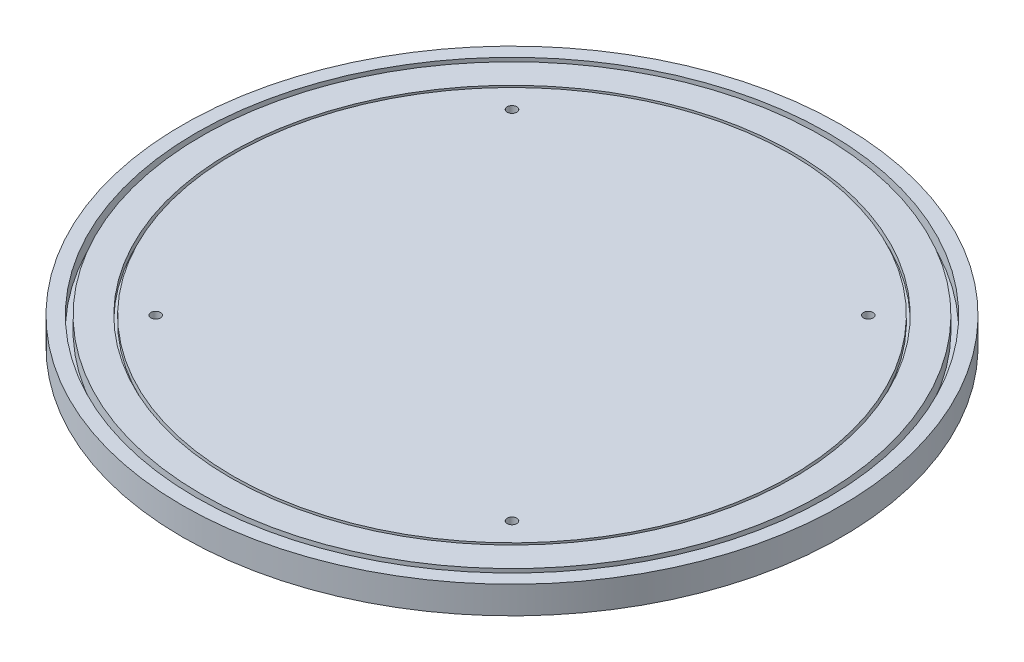
SolidWorks part; units mm, degrees
ref_plane "Plan de face" through (0, 0, 0) normal (0, 0, 1) x (1, 0, 0)
ref_plane "Plan de dessus" through (0, 0, 0) normal (0, 1, 0) x (1, 0, 0)
ref_plane "Plan de droite" through (0, 0, 0) normal (1, 0, 0) x (0, 0, -1)
sketch "Esquisse1" plane through (0, 0, 0) normal (1, 0, 0) x (0, 0, -1)
  line L4 (101.7544, 10) -> (101.7544, 7.8727)
  line L5 (101.7544, 7.8727) -> (102.7544, 7.8727)
  line L6 (102.7544, 7.8727) -> (102.7544, 10)
  line L7 (102.7544, 10) -> (113.2544, 10)
  line L8 (113.2544, 10) -> (113.2544, 5)
  line L9 (113.2544, 5) -> (115.2503, 5)
  line L10 (115.2503, 5) -> (115.2503, 10)
  line L11 (115.2503, 10) -> (120.2543, 10)
  line L12 (120.2543, 10) -> (120.2543, 0)
  line L14 (101.7544, 10) -> (0.0044, 10)
  line L15 (0.0044, 10) -> (0.0044, 0)
  line L16 (120.2543, 0) -> (0.0044, 0)
revolve "Révolution1" add sketch "Esquisse1" angle 360 about L15
sketch "Esquisse3" plane through (0, 10, 0) normal (0, 1, 0) x (1, 0, 0)
  circle A0 centre (0, 0) radius 15
extrude "Enlèv. mat.-Extru.1" [suppressed] cut sketch "Esquisse3" against normal blind 10
sketch "Esquisse4" plane through (0, 0, 0) normal (0, -1, 0) x (1, 0, 0)
  circle A0 centre (-25, -37) radius 3.5
  circle A1 centre (-40, 26) radius 3.5
  circle A2 centre (40, 26) radius 3.5
  circle A3 centre (30, -37) radius 3.5
extrude "Enlèv. mat.-Extru.2" [suppressed] cut sketch "Esquisse4" against normal blind 1
sketch "Esquisse5" plane through (0, 0, 0) normal (0, -1, 0) x (1, 0, 0)
  circle A0 centre (-65, 65) radius 1.75
  circle A1 centre (-65, -65) radius 1.75
  circle A2 centre (65, 65) radius 1.75
  circle A3 centre (65, -65) radius 1.75
  point P2 (0, 0)
extrude "Enlèv. mat.-Extru.3" cut sketch "Esquisse5" against normal blind 10
sketch "Esquisse6" [suppressed] plane through (0, 0, 0) normal (0, -1, 0) x (1, 0, 0)
